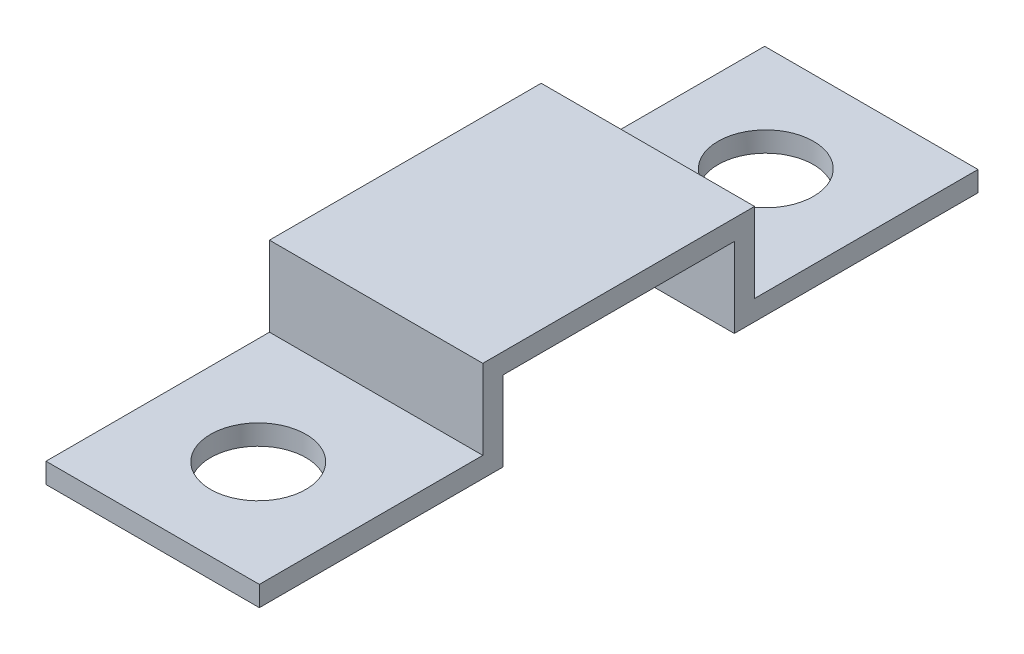
SolidWorks part; units mm, degrees
material "AISI 304"
ref_plane "前视基准面" through (0, 0, 0) normal (0, 0, 1) x (1, 0, 0)
ref_plane "上视基准面" through (0, 0, 0) normal (0, 1, 0) x (1, 0, 0)
ref_plane "右视基准面" through (0, 0, 0) normal (1, 0, 0) x (0, 0, -1)
other "Configuration Table"
sketch "草图5" plane through (0, 0, 0) normal (1, 0, 0) x (0, 0, -1)
  line L0 (0, 0) -> (0, 17100.1177) construction
  line L1 (12.1, 0) -> (-12.1, 0)
  line L2 (-12.1, 0) -> (-12.1, -7.1)
  line L3 (-12.1, -7.1) -> (-32, -7.1)
  line L4 (-32, -7.1) -> (-32, -8.9)
  line L5 (-32, -8.9) -> (-10.3, -8.9)
  line L6 (-10.3, -8.9) -> (-10.3, -1.8)
  line L7 (-10.3, -1.8) -> (10.3, -1.8)
  line L8 (10.3, -8.9) -> (10.3, -1.8)
  line L9 (32, -8.9) -> (10.3, -8.9)
  line L10 (32, -7.1) -> (32, -8.9)
  line L11 (12.1, -7.1) -> (32, -7.1)
  line L12 (12.1, 0) -> (12.1, -7.1)
  point P12 (0, -1.8)
  point P17 (0, 0)
  dimension "D1" = 1.8
  dimension "D2" = 1.8
  dimension "D3" = 1.8
  dimension "D4" = 7.1
  dimension "D5" = 20.6
  dimension "D6" = 64
extrude "凸台-拉伸5" add sketch "草图5" along normal blind 19
sketch "草图6" plane through (0, -7.1, 0) normal (0, 1, 0) x (1, 0, 0)
  line L0 (9.5, -32) -> (9.5, 32) construction
  line L1 (19, -32) -> (0, -32) construction
  line L2 (19, 32) -> (0, 32) construction
  line L3 (0, 0) -> (19, 0) construction
  line L4 (19, 12.1) -> (19, -12.1) construction
  circle A0 centre (9.5, -22.6) radius 4.25
  circle A1 centre (9.5, 22.6) radius 4.25
  dimension "D1" = 8.5
  dimension "D2" = 45.2
extrude "切除-拉伸1" cut sketch "草图6" against normal blind 19
